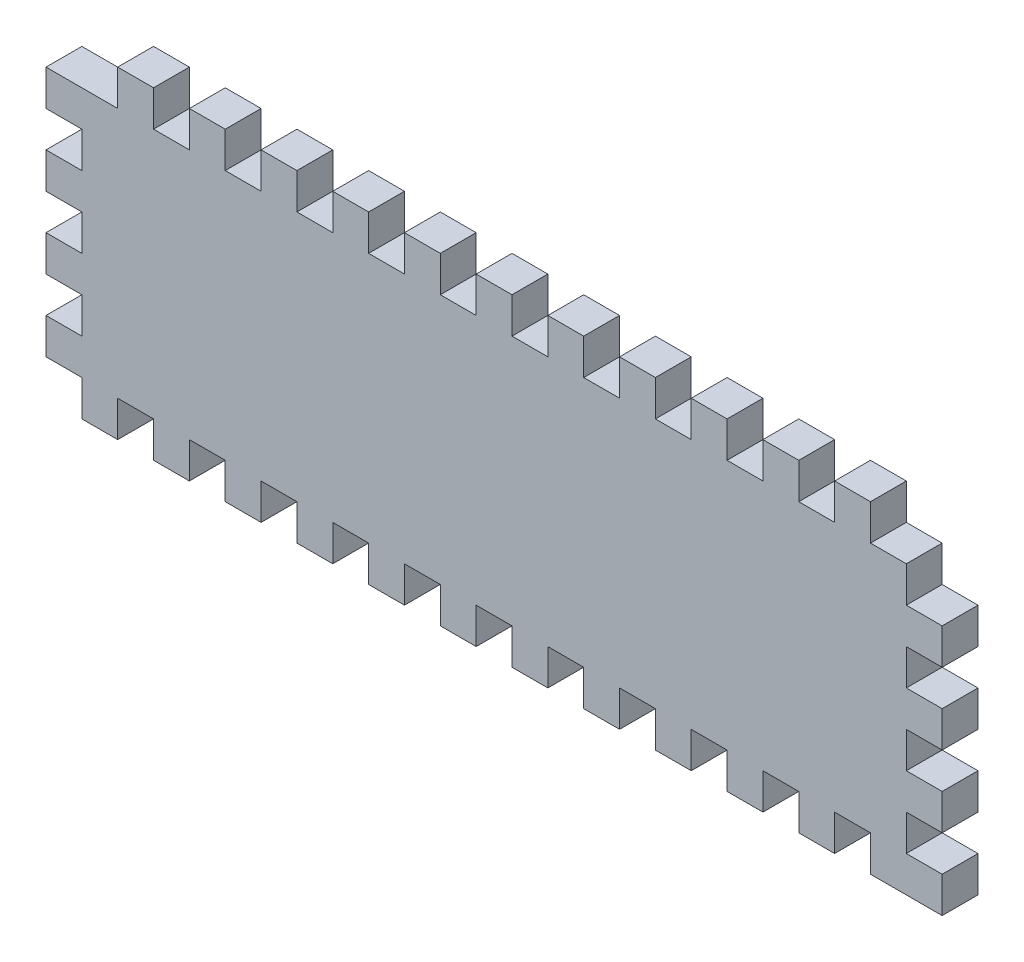
SolidWorks part; units mm, degrees
ref_plane "Front Plane" through (0, 0, 0) normal (0, 0, 1) x (1, 0, 0)
ref_plane "Top Plane" through (0, 0, 0) normal (0, 1, 0) x (1, 0, 0)
ref_plane "Right Plane" through (0, 0, 0) normal (1, 0, 0) x (0, 0, -1)
sketch "Sketch1" plane through (0, 0, 0) normal (0, 0, 1) x (1, 0, 0)
  line L3043 (282, 84) -> (285, 84)
  line L3044 (285, 84) -> (285, 81)
  line L3045 (285, 81) -> (291, 81)
  line L3046 (291, 81) -> (291, 84)
  line L3047 (291, 84) -> (288, 84)
  line L3048 (288, 84) -> (288, 87)
  line L3049 (288, 87) -> (291, 87)
  line L3050 (291, 87) -> (291, 90)
  line L3051 (291, 90) -> (288, 90)
  line L3052 (288, 90) -> (288, 93)
  line L3053 (288, 93) -> (291, 93)
  line L3054 (291, 93) -> (291, 96)
  line L3055 (291, 96) -> (288, 96)
  line L3056 (288, 96) -> (288, 99)
  line L3057 (288, 99) -> (291, 99)
  line L3058 (291, 99) -> (291, 102)
  line L3059 (291, 102) -> (288, 102)
  line L3060 (288, 102) -> (288, 105)
  line L3061 (288, 105) -> (285, 105)
  line L3062 (285, 105) -> (285, 108)
  line L3063 (285, 108) -> (282, 108)
  line L3064 (282, 108) -> (282, 105)
  line L3065 (282, 105) -> (279, 105)
  line L3066 (279, 105) -> (279, 108)
  line L3067 (279, 108) -> (276, 108)
  line L3068 (276, 108) -> (276, 105)
  line L3069 (276, 105) -> (273, 105)
  line L3070 (273, 105) -> (273, 108)
  line L3071 (273, 108) -> (270, 108)
  line L3072 (270, 108) -> (270, 105)
  line L3073 (270, 105) -> (267, 105)
  line L3074 (267, 105) -> (267, 108)
  line L3075 (267, 108) -> (264, 108)
  line L3076 (264, 108) -> (264, 105)
  line L3077 (264, 105) -> (261, 105)
  line L3078 (261, 105) -> (261, 108)
  line L3079 (261, 108) -> (258, 108)
  line L3080 (258, 108) -> (258, 105)
  line L3081 (258, 105) -> (255, 105)
  line L3082 (255, 105) -> (255, 108)
  line L3083 (255, 108) -> (252, 108)
  line L3084 (252, 108) -> (252, 105)
  line L3085 (252, 105) -> (249, 105)
  line L3086 (249, 105) -> (249, 108)
  line L3087 (249, 108) -> (246, 108)
  line L3088 (246, 108) -> (246, 105)
  line L3089 (246, 105) -> (243, 105)
  line L3090 (243, 105) -> (243, 108)
  line L3091 (243, 108) -> (240, 108)
  line L3092 (240, 108) -> (240, 105)
  line L3093 (240, 105) -> (237, 105)
  line L3094 (237, 105) -> (237, 108)
  line L3095 (237, 108) -> (234, 108)
  line L3096 (234, 108) -> (234, 105)
  line L3097 (234, 105) -> (231, 105)
  line L3098 (231, 105) -> (231, 108)
  line L3099 (231, 108) -> (228, 108)
  line L3100 (228, 108) -> (228, 105)
  line L3101 (228, 105) -> (225, 105)
  line L3102 (225, 105) -> (225, 108)
  line L3103 (225, 108) -> (222, 108)
  line L3104 (222, 108) -> (222, 105)
  line L3105 (222, 105) -> (216, 105)
  line L3106 (216, 105) -> (216, 102)
  line L3107 (216, 102) -> (219, 102)
  line L3108 (219, 102) -> (219, 99)
  line L3109 (219, 99) -> (216, 99)
  line L3110 (216, 99) -> (216, 96)
  line L3111 (216, 96) -> (219, 96)
  line L3112 (219, 96) -> (219, 93)
  line L3113 (219, 93) -> (216, 93)
  line L3114 (216, 93) -> (216, 90)
  line L3115 (216, 90) -> (219, 90)
  line L3116 (219, 90) -> (219, 87)
  line L3117 (219, 87) -> (216, 87)
  line L3118 (216, 87) -> (216, 84)
  line L3119 (216, 84) -> (219, 84)
  line L3120 (219, 84) -> (219, 81)
  line L3121 (219, 81) -> (222, 81)
  line L3122 (222, 81) -> (222, 84)
  line L3123 (222, 84) -> (225, 84)
  line L3124 (225, 84) -> (225, 81)
  line L3125 (225, 81) -> (228, 81)
  line L3126 (228, 81) -> (228, 84)
  line L3127 (228, 84) -> (231, 84)
  line L3128 (231, 84) -> (231, 81)
  line L3129 (231, 81) -> (234, 81)
  line L3130 (234, 81) -> (234, 84)
  line L3131 (234, 84) -> (237, 84)
  line L3132 (237, 84) -> (237, 81)
  line L3133 (237, 81) -> (240, 81)
  line L3134 (240, 81) -> (240, 84)
  line L3135 (240, 84) -> (243, 84)
  line L3136 (243, 84) -> (243, 81)
  line L3137 (243, 81) -> (246, 81)
  line L3138 (246, 81) -> (246, 84)
  line L3139 (246, 84) -> (249, 84)
  line L3140 (249, 84) -> (249, 81)
  line L3141 (249, 81) -> (252, 81)
  line L3142 (252, 81) -> (252, 84)
  line L3143 (252, 84) -> (255, 84)
  line L3144 (255, 84) -> (255, 81)
  line L3145 (255, 81) -> (258, 81)
  line L3146 (258, 81) -> (258, 84)
  line L3147 (258, 84) -> (261, 84)
  line L3148 (261, 84) -> (261, 81)
  line L3149 (261, 81) -> (264, 81)
  line L3150 (264, 81) -> (264, 84)
  line L3151 (264, 84) -> (267, 84)
  line L3152 (267, 84) -> (267, 81)
  line L3153 (267, 81) -> (270, 81)
  line L3154 (270, 81) -> (270, 84)
  line L3155 (270, 84) -> (273, 84)
  line L3156 (273, 84) -> (273, 81)
  line L3157 (273, 81) -> (276, 81)
  line L3158 (276, 81) -> (276, 84)
  line L3159 (276, 84) -> (279, 84)
  line L3160 (279, 84) -> (279, 81)
  line L3161 (279, 81) -> (282, 81)
  line L3162 (282, 81) -> (282, 84)
extrude "Boss-Extrude1" add sketch "Sketch1" along normal blind 3
